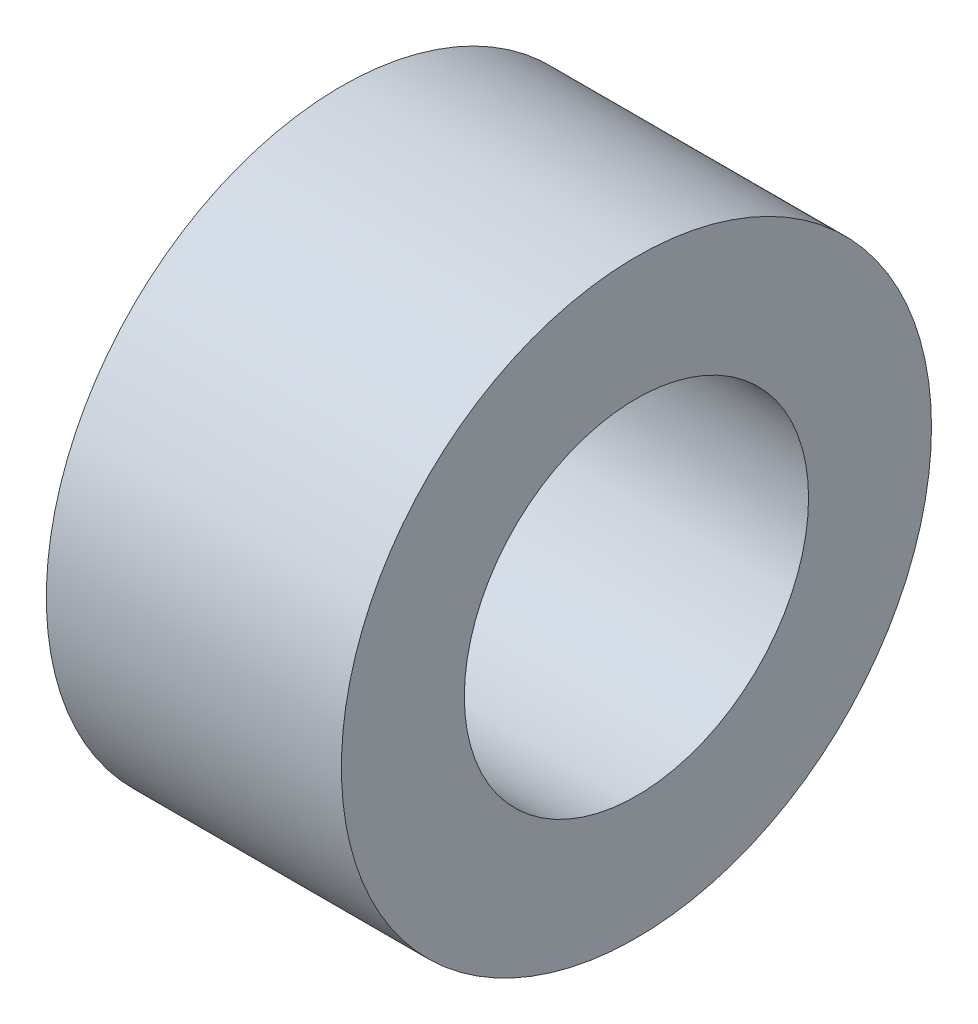
SolidWorks part; units mm, degrees
material "Plain Carbon Steel"
ref_plane "Front Plane" through (0, 0, 0) normal (0, 0, 1) x (1, 0, 0)
ref_plane "Top Plane" through (0, 0, 0) normal (0, 1, 0) x (1, 0, 0)
ref_plane "Right Plane" through (0, 0, 0) normal (1, 0, 0) x (0, 0, -1)
sketch "Sketch1" plane through (0, 0, 0) normal (1, 0, 0) x (0, 0, -1)
  circle A0 centre (0, 0) radius 6
  circle A1 centre (0, 0) radius 3.5
  dimension "D1" = 7
  dimension "12" = 12
extrude "Boss-Extrude1" add sketch "Sketch1" along normal mid plane 6 contours A0 A1
